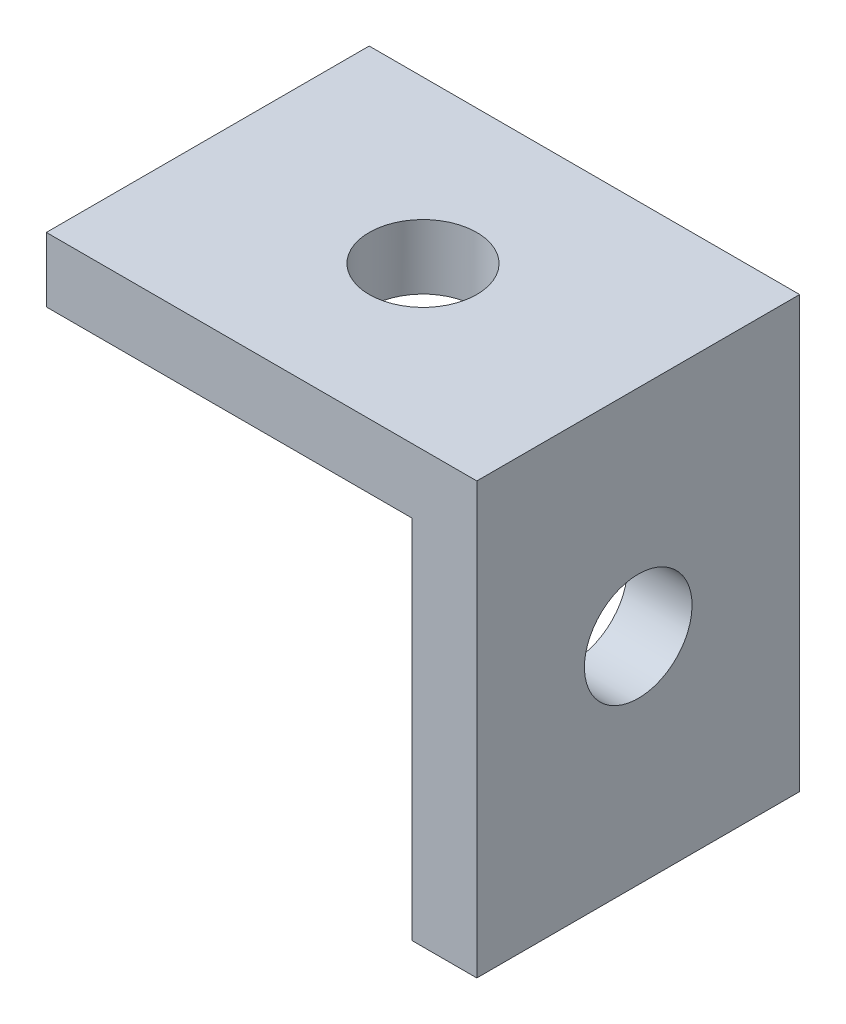
SolidWorks part; units mm, degrees
ref_plane "정면" through (0, 0, 0) normal (0, 0, 1) x (1, 0, 0)
ref_plane "윗면" through (0, 0, 0) normal (0, 1, 0) x (1, 0, 0)
ref_plane "우측면" through (0, 0, 0) normal (1, 0, 0) x (0, 0, -1)
sketch "스케치1" plane through (0, 0, 0) normal (0, 0, 1) x (1, 0, 0)
  line L0 (0, 0) -> (23, 0)
  line L1 (23, 0) -> (23, -23)
  line L2 (23, -23) -> (20, -23)
  line L3 (20, -23) -> (20, -3)
  line L4 (20, -3) -> (0, -3)
  line L5 (0, -3) -> (0, 0)
  point P3 (21.5, -23)
  dimension "D1" = 3
  dimension "D2" = 3
  dimension "D3" = 23
  dimension "D4" = 23
extrude "보스-돌출1" add sketch "스케치1" along normal blind 15
sketch "스케치2" plane through (0, 0, 0) normal (0, 1, 0) x (1, 0, 0)
  line L0 (23, -15) -> (23, 0) construction
  circle A0 centre (13, -7.5) radius 2.5
  dimension "D1" = 10
extrude "컷-돌출1" cut sketch "스케치2" against normal blind 15
sketch "스케치3" plane through (23, 0, 0) normal (1, 0, 0) x (0, 0, -1)
  line L0 (-15, 0) -> (0, 0) construction
  circle A0 centre (-7.5, -10) radius 2.5
  dimension "D1" = 10
extrude "컷-돌출2" cut sketch "스케치3" against normal blind 15
sketch "스케치4" plane through (23, 0, 0) normal (1, 0, 0) x (0, 0, -1)
  line L0 (-15, 0) -> (0, 0) construction
  line L1 (-19.134, -20) -> (3.8051, -20)
  line L2 (-19.134, -20) -> (-19.134, -27.1778)
  line L3 (-19.134, -27.1778) -> (3.8051, -27.1778)
  line L4 (3.8051, -20) -> (3.8051, -27.1778)
  dimension "D1" = 20
extrude "컷-돌출3" cut sketch "스케치4" against normal blind 15
sketch "스케치5" plane through (0, 0, 0) normal (0, 1, 0) x (1, 0, 0)
  line L0 (23, -15) -> (23, 0) construction
  line L1 (-0.4897, 1.3628) -> (3, 1.3628)
  line L2 (-0.4897, 1.3628) -> (-0.4897, -16.0855)
  line L3 (-0.4897, -16.0855) -> (3, -16.0855)
  line L4 (3, 1.3628) -> (3, -16.0855)
  dimension "D1" = 20
extrude "컷-돌출4" cut sketch "스케치5" against normal blind 15
